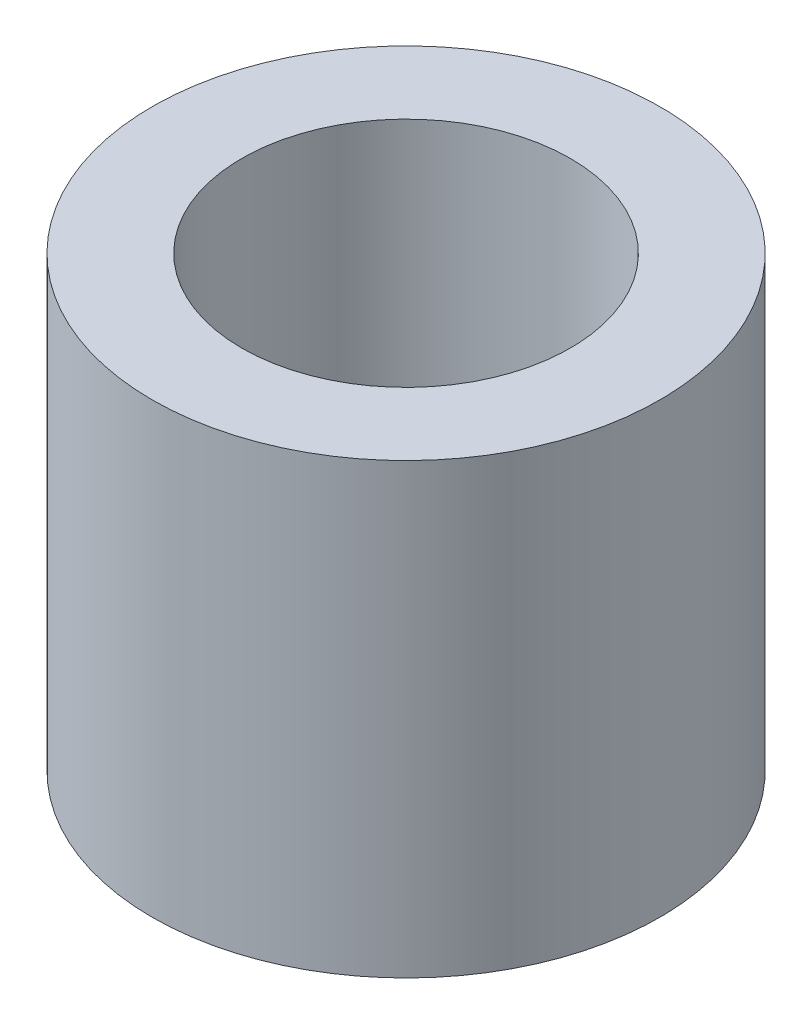
SolidWorks part; units mm, degrees
ref_plane "Front Plane" through (0, 0, 0) normal (0, 0, 1) x (1, 0, 0)
ref_plane "Top Plane" through (0, 0, 0) normal (0, 1, 0) x (1, 0, 0)
ref_plane "Right Plane" through (0, 0, 0) normal (1, 0, 0) x (0, 0, -1)
sketch "Sketch1" plane through (0, 0, 0) normal (0, 1, 0) x (1, 0, 0)
  circle A0 centre (0, 0) radius 1.7
  circle A1 centre (0, 0) radius 1.1
  dimension "D1" = 2.2
  dimension "D2" = 3.4
extrude "Boss-Extrude1" add sketch "Sketch1" along normal blind 3
